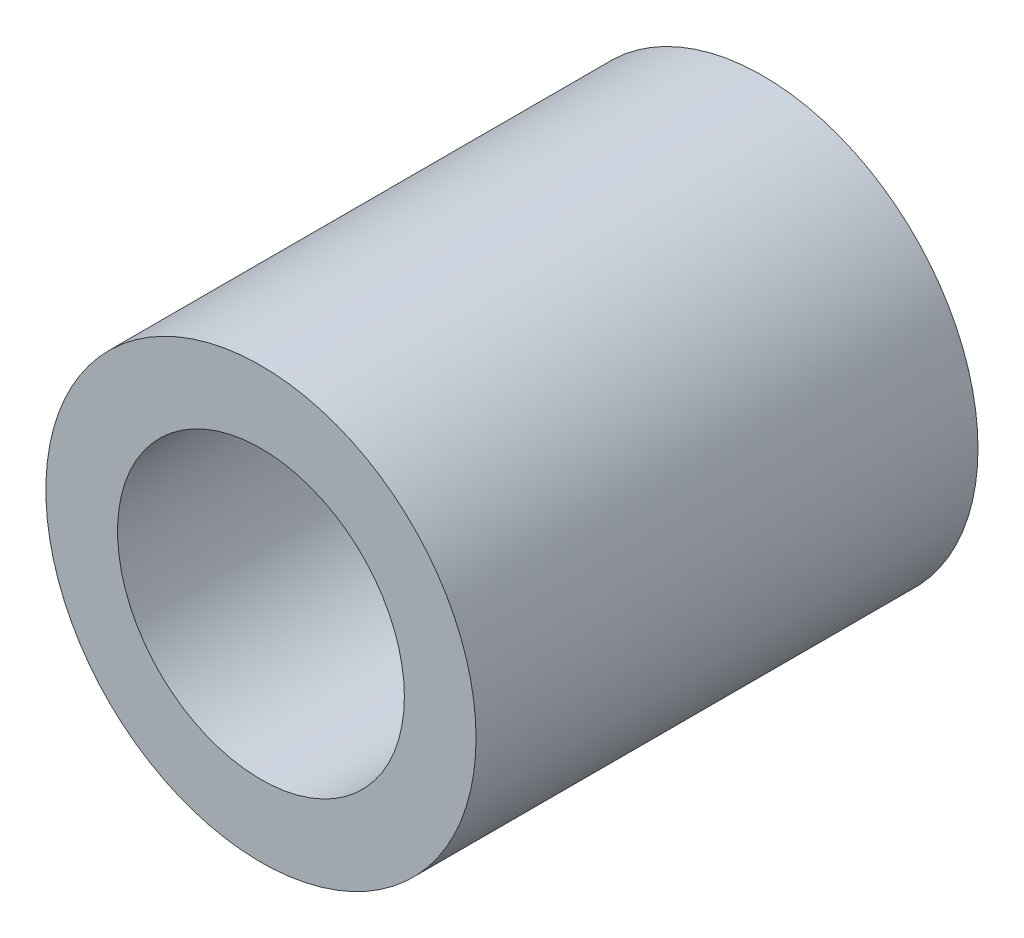
SolidWorks part; units mm, degrees
material "Thornel Mat VMA"
ref_plane "前视基准面" through (0, 0, 0) normal (0, 0, 1) x (1, 0, 0)
ref_plane "上视基准面" through (0, 0, 0) normal (0, 1, 0) x (1, 0, 0)
ref_plane "右视基准面" through (0, 0, 0) normal (1, 0, 0) x (0, 0, -1)
sketch "草图1" plane through (0, 0, 0) normal (0, 0, 1) x (1, 0, 0)
  circle A0 centre (0, 0) radius 2
  circle A1 centre (0, 0) radius 3
  dimension "D1" = 4
  dimension "D2" = 6
extrude "凸台-拉伸1" add sketch "草图1" along normal blind 7
